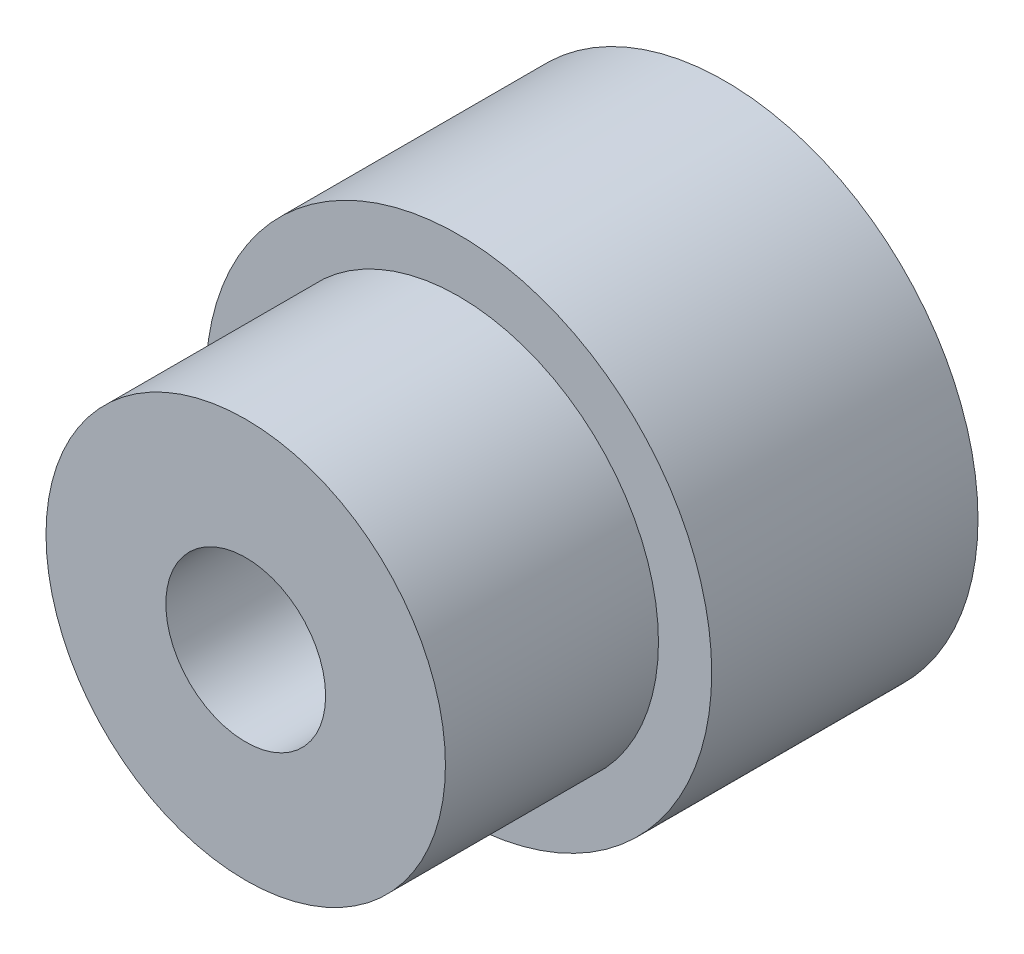
SolidWorks part; units mm, degrees
ref_plane "前视基准面" through (0, 0, 0) normal (0, 0, 1) x (1, 0, 0)
ref_plane "上视基准面" through (0, 0, 0) normal (0, 1, 0) x (1, 0, 0)
ref_plane "右视基准面" through (0, 0, 0) normal (1, 0, 0) x (0, 0, -1)
sketch "草图1" plane through (0, 0, 0) normal (0, 0, 1) x (1, 0, 0)
  circle A0 centre (0, 0) radius 9.5
  circle A1 centre (0, 0) radius 3
extrude "凸台-拉伸1" add sketch "草图1" along normal blind 10
sketch "草图2" plane through (0, 0, 10) normal (0, 0, 1) x (1, 0, 0)
  circle A0 centre (0, 0) radius 7.5
  circle A1 centre (0, 0) radius 3
extrude "凸台-拉伸2" add sketch "草图2" along normal blind 8
